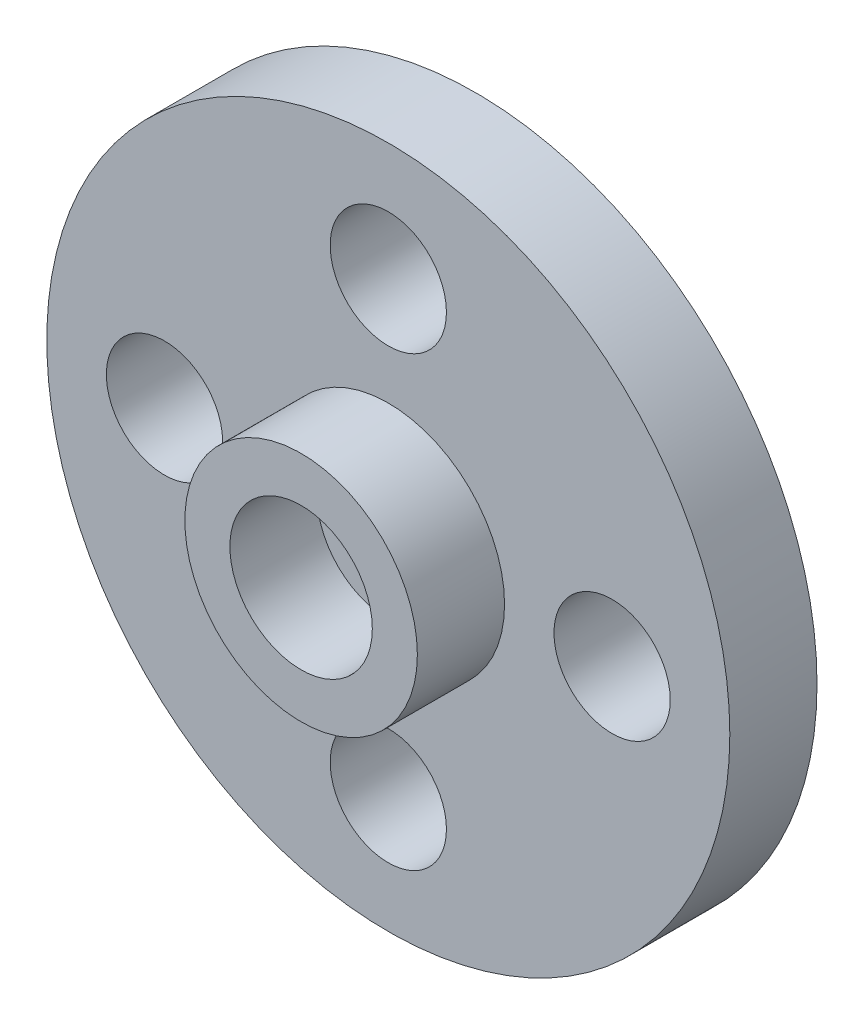
SolidWorks part; units mm, degrees
ref_plane "Ebene vorne" through (0, 0, 0) normal (0, 0, 1) x (1, 0, 0)
ref_plane "Ebene oben" through (0, 0, 0) normal (0, 1, 0) x (1, 0, 0)
ref_plane "Ebene rechts" through (0, 0, 0) normal (1, 0, 0) x (0, 0, -1)
sketch "Skizze1" plane through (0, 0, 0) normal (0, 0, 1) x (1, 0, 0)
  circle A0 centre (0, 0) radius 11.75
  dimension "D1" = 23.5
extrude "Aufsatz-Linear austragen1" add sketch "Skizze1" against normal blind 3
sketch "Skizze2" plane through (0, 0, 0) normal (0, 0, 1) x (1, 0, 0)
  circle A0 centre (0, 0) radius 4
  circle A1 centre (0, 0) radius 2.45
  dimension "D1" = 4.9
  dimension "D2" = 8
extrude "Aufsatz-Linear austragen2" add sketch "Skizze2" along normal blind 3
sketch "Skizze3" plane through (0, 0, 0) normal (0, 0, 1) x (1, 0, 0)
  circle A0 centre (0, 7.7) radius 2
  circle A1 centre (7.7, 0) radius 2
  circle A2 centre (0, -7.7) radius 2
  circle A3 centre (-7.7, 0) radius 2
  point P12 (0, 0)
  point P14 (0, 0)
  dimension "D1" = 4
  dimension "D3" = 4
  dimension "D2" = 7.7
extrude "Schnitt-Linear austragen1" cut sketch "Skizze3" against normal up to next
sketch "Skizze4" plane through (0, 0, 0) normal (0, 0, 1) x (1, 0, 0)
  line L0 (-5.7, 0) -> (-4, 0)
  circle A0 centre (-7.7, 0) radius 2 construction
  circle A1 centre (0, 0) radius 4 construction
  point P0 (-5.7, 0)
  point P1 (-4, 0)
  dimension "D1" = 1.7
